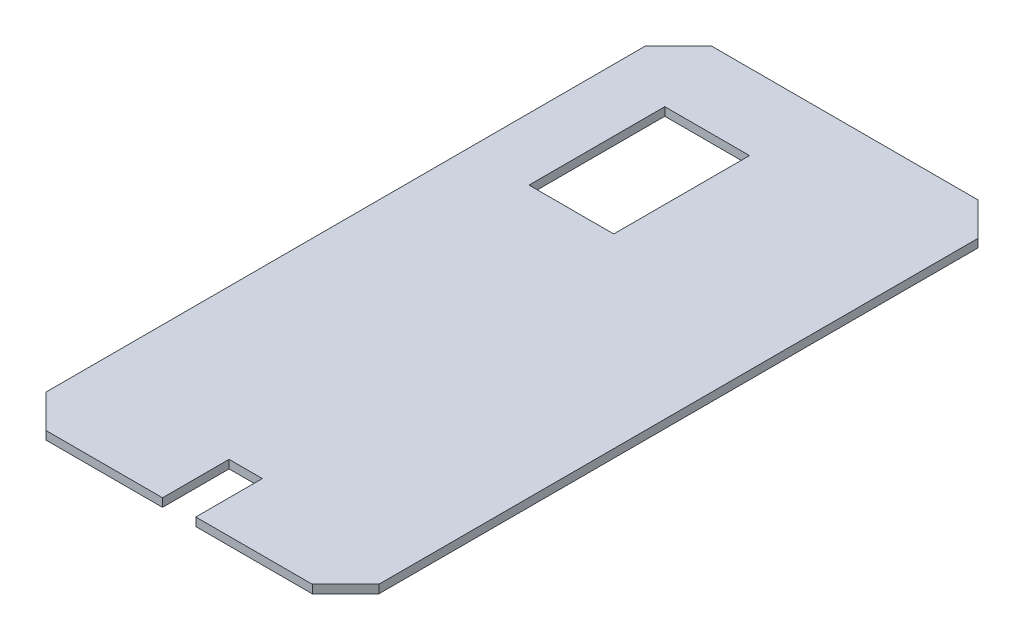
SolidWorks part; units mm, degrees
ref_plane "Front Plane" through (0, 0, 0) normal (0, 0, 1) x (1, 0, 0)
ref_plane "Top Plane" through (0, 0, 0) normal (0, 1, 0) x (1, 0, 0)
ref_plane "Right Plane" through (0, 0, 0) normal (1, 0, 0) x (0, 0, -1)
sketch "Sketch2" plane through (0, 0, 0) normal (0, 1, 0) x (1, 0, 0)
  line L0 (0, 12.7) -> (0, 241.3)
  line L1 (12.7, 254) -> (114.3, 254)
  line L2 (127, 241.3) -> (127, 12.7)
  line L3 (114.3, 0) -> (12.7, 0)
  line L4 (0, 241.3) -> (12.7, 254)
  line L5 (114.3, 254) -> (127, 241.3)
  line L6 (127, 12.7) -> (114.3, 0)
  line L7 (12.7, 0) -> (0, 12.7)
  line L8 (63.5, 254) -> (63.5, -26.6567) construction
  line L10 (0, 127) -> (136.1553, 127) construction
  line L17 (57.15, 25.4) -> (69.85, 25.4)
  line L18 (57.15, 25.4) -> (57.15, 0)
  line L19 (57.15, 0) -> (69.85, 0)
  line L20 (69.85, 25.4) -> (69.85, 0)
  line L21 (57.15, 25.4) -> (69.85, 0) construction
  line L22 (57.15, 0) -> (69.85, 25.4) construction
  line L23 (23.7519, 225.0527) -> (56.0622, 225.0527)
  line L24 (23.7519, 225.0527) -> (23.7519, 173.2475)
  line L25 (23.7519, 173.2475) -> (56.0622, 173.2475)
  line L26 (56.0622, 225.0527) -> (56.0622, 173.2475)
  line L27 (23.7519, 225.0527) -> (56.0622, 173.2475) construction
  line L28 (23.7519, 173.2475) -> (56.0622, 225.0527) construction
  point P0 (63.5, 127)
  point P1 (39.907, 199.1501)
  point P3 (63.5, 12.7)
  point P19 (0, 0)
  point P20 (40.0289, 193.833)
  point P21 (0, 0)
  point P22 (0, 0)
  point P23 (0, 0)
  point P25 (39.907, 199.1501)
  point P37 (127, 127)
  point P42 (63.5, 0)
  dimension "D14" = 101.6
  dimension "D16" = 12.7
  dimension "D17" = 254
  dimension "D22" = 228.6
  dimension "D36" = 101.6
  dimension "D37" = 228.6
  dimension "D7" = 127
  dimension "D15" = 12.7
  dimension "D4" = 25.4
  dimension "D5" = 12.7
extrude "Boss-Extrude1" add sketch "Sketch2" along normal blind 3.175
